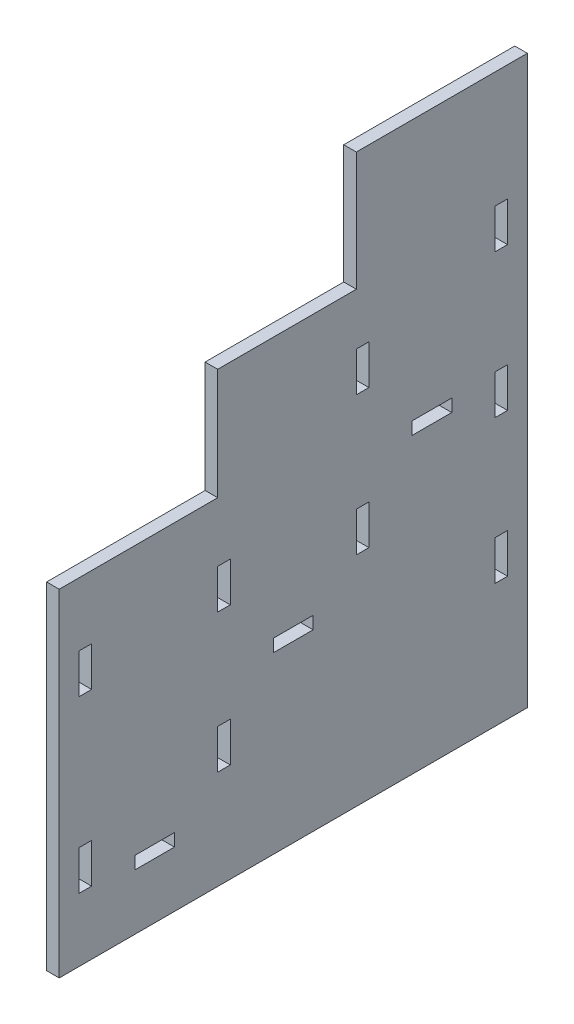
SolidWorks part; units mm, degrees
ref_plane "Alzado" through (0, 0, 0) normal (0, 0, 1) x (1, 0, 0)
ref_plane "Planta" through (0, 0, 0) normal (0, 1, 0) x (1, 0, 0)
ref_plane "Vista lateral" through (0, 0, 0) normal (1, 0, 0) x (0, 0, -1)
sketch "Croquis1" plane through (0, 0, 0) normal (1, 0, 0) x (0, 0, -1)
  line L0 (-117.243, -155.2025) -> (-117.243, 14.7975)
  line L1 (-117.243, 14.7975) -> (-47.243, 14.7975)
  line L2 (-47.243, 14.7975) -> (-47.243, 70.9575)
  line L3 (-47.243, 70.9575) -> (22.757, 70.9575)
  line L4 (22.757, 70.9575) -> (22.757, 130.9575)
  line L5 (22.757, 130.9575) -> (92.757, 130.9575)
  line L6 (92.757, 130.9575) -> (92.757, -155.2025)
  line L7 (92.757, -155.2025) -> (-117.243, -155.2025)
  dimension "D1" = 170
  dimension "D2" = 210
  dimension "D3" = 60
  dimension "D4" = 70
  dimension "D5" = 70
  dimension "D6" = 70
  dimension "D7" = 56.16
extrude "Saliente-Extruir1" add sketch "Croquis1" along normal blind 6.35
sketch "Croquis2" plane through (0, 0, 0) normal (-1, 0, 0) x (0, 0, 1)
  line L0 (117.243, 14.7975) -> (117.243, -155.2025) construction
  line L1 (117.243, -17.2025) -> (110.893, -17.2025)
  line L2 (117.243, -17.2025) -> (117.243, -37.2025)
  line L3 (117.243, -37.2025) -> (110.893, -37.2025)
  line L4 (110.893, -17.2025) -> (110.893, -37.2025)
  line L5 (47.243, 14.7975) -> (117.243, 14.7975) construction
  line L6 (117.243, -70.2025) -> (-92.757, -70.2025) construction
  line L7 (-92.757, -155.2025) -> (-92.757, 130.9575) construction
  line L8 (110.893, -123.2025) -> (110.893, -103.2025)
  line L9 (117.243, -103.2025) -> (110.893, -103.2025)
  line L10 (117.243, -123.2025) -> (117.243, -103.2025)
  line L11 (117.243, -123.2025) -> (110.893, -123.2025)
  line L12 (-22.757, 70.9575) -> (-22.757, -135.2025) construction
  line L13 (117.243, -155.2025) -> (-92.757, -155.2025) construction
  line L14 (47.243, 14.7975) -> (47.243, -135.2025) construction
  line L15 (117.243, -135.2025) -> (-92.757, -135.2025) construction
  line L16 (-92.757, -128.8525) -> (117.243, -128.8525) construction
  line L17 (47.243, -60.2025) -> (-92.757, -60.2025) construction
  line L18 (47.243, -15.2025) -> (40.893, -15.2025)
  line L19 (47.243, -15.2025) -> (47.243, -35.2025)
  line L20 (47.243, -35.2025) -> (40.893, -35.2025)
  line L21 (40.893, -15.2025) -> (40.893, -35.2025)
  line L22 (40.893, -105.2025) -> (40.893, -85.2025)
  line L23 (47.243, -85.2025) -> (40.893, -85.2025)
  line L24 (47.243, -105.2025) -> (47.243, -85.2025)
  line L25 (47.243, -105.2025) -> (40.893, -105.2025)
  line L27 (-22.757, 44.7975) -> (-29.107, 44.7975)
  line L28 (-22.757, 44.7975) -> (-22.757, 24.7975)
  line L29 (-22.757, 24.7975) -> (-29.107, 24.7975)
  line L30 (-29.107, 44.7975) -> (-29.107, 24.7975)
  line L32 (-22.757, -25.2025) -> (-29.107, -25.2025)
  line L33 (-22.757, -25.2025) -> (-22.757, -45.2025)
  line L34 (-22.757, -45.2025) -> (-29.107, -45.2025)
  line L35 (-29.107, -25.2025) -> (-29.107, -45.2025)
  dimension "D1" = 6.35
  dimension "D2" = 20
  dimension "D3" = 32
  dimension "D4" = 20
  dimension "D5" = 6.35
  dimension "D6" = 30
  dimension "D7" = 200
  dimension "D8" = 50
extrude "Cortar-Extruir1" cut sketch "Croquis2" against normal blind 10
sketch "Croquis3" plane through (0, 0, 0) normal (1, 0, 0) x (0, 0, -1)
  line L0 (-117.243, -155.2025) -> (92.757, -155.2025) construction
  line L1 (92.757, 130.9575) -> (99.107, 130.9575)
  line L2 (92.757, 130.9575) -> (92.757, -155.2025)
  line L3 (92.757, -155.2025) -> (99.107, -155.2025)
  line L4 (99.107, 130.9575) -> (99.107, -155.2025)
  dimension "D1" = 6.35
extrude "Saliente-Extruir2" add sketch "Croquis3" along normal blind 6.35
sketch "Croquis4" plane through (0, 0, 0) normal (-1, 0, 0) x (0, 0, 1)
  line L0 (-99.107, -0.2025) -> (-92.757, -0.2025)
  line L1 (-99.107, -155.2025) -> (-99.107, 130.9575) construction
  line L2 (-99.107, 52.2975) -> (-92.757, 52.2975)
  line L3 (-99.107, 52.2975) -> (-99.107, 72.2975)
  line L4 (-99.107, 72.2975) -> (-92.757, 72.2975)
  line L5 (-92.757, 52.2975) -> (-92.757, 72.2975)
  line L6 (-99.107, 52.2975) -> (-92.757, 72.2975) construction
  line L7 (-99.107, 72.2975) -> (-92.757, 52.2975) construction
  line L9 (-99.107, -0.2025) -> (-99.107, -20.2025)
  line L10 (-99.107, -20.2025) -> (-92.757, -20.2025)
  line L11 (-92.757, -0.2025) -> (-92.757, -20.2025)
  line L12 (-99.107, -0.2025) -> (-92.757, -20.2025) construction
  line L13 (-99.107, -20.2025) -> (-92.757, -0.2025) construction
  line L14 (-99.107, -72.7025) -> (-92.757, -72.7025)
  line L15 (-99.107, -72.7025) -> (-99.107, -92.7025)
  line L16 (-99.107, -92.7025) -> (-92.757, -92.7025)
  line L17 (-92.757, -72.7025) -> (-92.757, -92.7025)
  line L18 (-99.107, -72.7025) -> (-92.757, -92.7025) construction
  line L19 (-99.107, -92.7025) -> (-92.757, -72.7025) construction
  line L21 (117.243, -155.2025) -> (-99.107, -155.2025) construction
  point P2 (-95.932, 62.2975)
  point P9 (-95.932, -10.2025)
  point P14 (-95.932, -82.7025)
  dimension "D1" = 20
  dimension "D2" = 6.35
  dimension "D3" = 72.5
  dimension "D4" = 72.5
  dimension "D5" = 72.5
extrude "Cortar-Extruir2" cut sketch "Croquis4" against normal blind 6.35
sketch "Croquis5" plane through (6.35, 0, 0) normal (1, 0, 0) x (0, 0, -1)
  line L0 (-117.243, -155.2025) -> (99.107, -155.2025) construction
  line L1 (-89.063, -120.6925) -> (-69.063, -120.6925)
  line L2 (-89.063, -120.6925) -> (-89.063, -127.0425)
  line L3 (-89.063, -127.0425) -> (-69.063, -127.0425)
  line L4 (-69.063, -120.6925) -> (-69.063, -127.0425)
  line L5 (-19.063, -60.6925) -> (0.937, -60.6925)
  line L6 (-19.063, -60.6925) -> (-19.063, -67.0425)
  line L7 (-19.063, -67.0425) -> (0.937, -67.0425)
  line L8 (0.937, -60.6925) -> (0.937, -67.0425)
  line L9 (50.937, -0.6925) -> (70.937, -0.6925)
  line L10 (50.937, -0.6925) -> (50.937, -7.0425)
  line L11 (50.937, -7.0425) -> (70.937, -7.0425)
  line L12 (70.937, -0.6925) -> (70.937, -7.0425)
  line L13 (-117.243, -123.2025) -> (-117.243, -155.2025) construction
  point P17 (60.937, -7.0425)
  dimension "D1" = 20
  dimension "D2" = 6.35
  dimension "D3" = 28.16
  dimension "D4" = 28.18
  dimension "D5" = 60
  dimension "D6" = 50
  dimension "D7" = 60
  dimension "D8" = 50
extrude "Cortar-Extruir3" cut sketch "Croquis5" against normal blind 10
sketch "Croquis6" plane through (0, 0, 0) normal (1, 0, 0) x (0, 0, -1)
  line L0 (-117.243, -155.2025) -> (99.107, -155.2025) construction
  line L1 (99.107, 130.9575) -> (109.107, 130.9575)
  line L2 (99.107, 130.9575) -> (99.107, -155.2025)
  line L3 (99.107, -155.2025) -> (109.107, -155.2025)
  line L4 (109.107, 130.9575) -> (109.107, -155.2025)
  line L5 (-117.243, 14.7975) -> (-127.243, 14.7975)
  line L6 (-117.243, 14.7975) -> (-117.243, -155.2025)
  line L7 (-117.243, -155.2025) -> (-127.243, -155.2025)
  line L8 (-127.243, 14.7975) -> (-127.243, -155.2025)
  dimension "D1" = 10
extrude "Saliente-Extruir3" add sketch "Croquis6" along normal up to surface (6.35 mm away) up to face at (6.35, -123.8675, 79.063)
